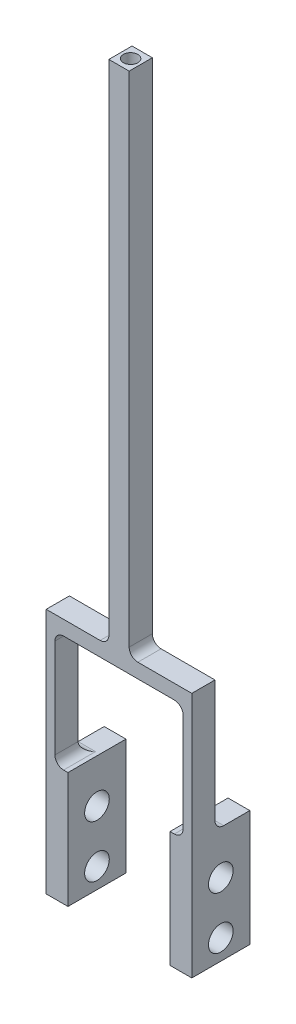
SolidWorks part; units mm, degrees
ref_plane "Front" through (0, 0, 0) normal (0, 0, 1) x (1, 0, 0)
ref_plane "Top" through (0, 0, 0) normal (0, 1, 0) x (1, 0, 0)
ref_plane "Right" through (0, 0, 0) normal (1, 0, 0) x (0, 0, -1)
sketch "Sketch6" plane through (0, 0, 0) normal (0, 0, 1) x (1, 0, 0)
  line L0 (0, 8.601) -> (0, -9.0458) construction
  line L1 (-17.6, 0) -> (17.6, 0)
  line L2 (-17.6, 0) -> (-17.6, 260)
  line L3 (-17.6, 260) -> (17.6, 260)
  line L4 (17.6, 0) -> (17.6, 260)
  line L5 (-17.6, 0) -> (-25.1, 0)
  line L6 (-17.6, 0) -> (-17.6, 40)
  line L7 (-17.6, 40) -> (-25.1, 40)
  line L8 (-25.1, 0) -> (-25.1, 40)
  line L9 (17.6, 40) -> (25.1, 40)
  line L10 (25.1, 0) -> (25.1, 40)
  line L11 (17.6, 0) -> (25.1, 0)
  line L12 (17.6, 0) -> (17.6, 40)
  line L13 (25.1, 80) -> (22.1, 80)
  line L14 (-25.1, 40) -> (-22.1, 40)
  line L15 (-25.1, 40) -> (-25.1, 80)
  line L16 (-25.1, 80) -> (-22.1, 80)
  line L17 (-22.1, 40) -> (-22.1, 80)
  line L18 (22.1, 40) -> (22.1, 80)
  line L19 (25.1, 40) -> (22.1, 40)
  line L20 (25.1, 40) -> (25.1, 80)
  line L21 (25.1, 85) -> (17.6, 85)
  line L22 (-25.1, 80) -> (-17.6, 80)
  line L23 (-25.1, 80) -> (-25.1, 85)
  line L24 (-25.1, 85) -> (-17.6, 85)
  line L25 (-17.6, 80) -> (-17.6, 85)
  line L26 (17.6, 80) -> (17.6, 85)
  line L27 (25.1, 80) -> (17.6, 80)
  line L28 (25.1, 80) -> (25.1, 85)
  line L29 (-17.6, 80) -> (17.6, 80)
  line L30 (-17.6, 85) -> (-3.5, 85)
  line L31 (-3.5, 85) -> (3.5, 85)
  line L32 (-3.5, 85) -> (-3.5, 260)
  line L33 (-3.5, 260) -> (3.5, 260)
  line L34 (3.5, 85) -> (3.5, 260)
  line L35 (17.6, 85) -> (3.5, 85)
  point P1 (0, 0)
  point P4 (0, 0)
  point P30 (0, 85)
  point P34 (0, 0)
  point P35 (0, 0)
  dimension "D1" = 260
  dimension "D2" = 35.2
  dimension "D3" = 40
  dimension "D4" = 7.5
  dimension "D5" = 40
  dimension "D6" = 3
  dimension "D7" = 5
  dimension "D8" = 7
extrude "Boss-Extrude4" add sketch "Sketch6" along normal mid plane 20
sketch "Sketch7" plane through (0, 0, 0) normal (1, 0, 0) x (0, 0, -1)
  line L0 (-10, 0) -> (10, 0) construction
  line L1 (-10, 0) -> (10, 0) construction
  circle A0 centre (0, 7) radius 4.25
  circle A1 centre (0, 25) radius 4.25
  point P6 (0, 0)
  point P8 (0, 0)
  dimension "D1" = 8.5
  dimension "D2" = 7
  dimension "D3" = 18
extrude "Cut-Extrude2" cut sketch "Sketch7" against normal through all both and the other way through all
sketch "Sketch11" plane through (0, 0, 0) normal (1, 0, 0) x (0, 0, -1)
  line L0 (-10, 85) -> (-10, 260) construction
  line L1 (16.6439, 260) -> (-2, 260)
  line L2 (16.6439, 260) -> (16.6439, 40)
  line L3 (16.6439, 40) -> (-2, 40)
  line L4 (-2, 260) -> (-2, 40)
  line L7 (-10, 260) -> (10, 260) construction
  point P7 (0, 0)
  point P9 (16.6439, 247.8145)
  dimension "D1" = 8
  dimension "D2" = 40
extrude "Cut-Extrude4" cut sketch "Sketch11" against normal through all both and the other way through all
sketch "Sketch12" plane through (0, 260, 0) normal (0, 1, 0) x (1, 0, 0)
  line L0 (-1.693, -6) -> (1.3044, -6) construction
  line L1 (0, -5.2733) -> (0, -7.1605) construction
  line L4 (3.5, -2) -> (-3.5, -2)
  line L5 (-3.5, -2) -> (-3.5, -10)
  line L6 (-3.5, -10) -> (3.5, -10)
  line L7 (3.5, -10) -> (3.5, -2)
  line L8 (3.5, -2) -> (-3.5, -2) construction
  line L9 (-3.5, -2) -> (-3.5, -10) construction
  line L10 (-3.5, -10) -> (3.5, -10) construction
  line L11 (3.5, -10) -> (3.5, -2) construction
  circle A0 centre (0, -6) radius 2.5
  dimension "D2" = 5
  dimension "D1" = 0
extrude "Cut-Extrude5" cut sketch "Sketch12" against normal blind 20 and the other way through all
fillet "Fillet3" radius 3 7 edges at (-22.1, 80, 6) (-23.6, 40, 2) (-22.1, 40, 6) (22.1, 80, 6) (22.1, 40, 6) (-3.5, 85, 6) (3.5, 85, 6)
